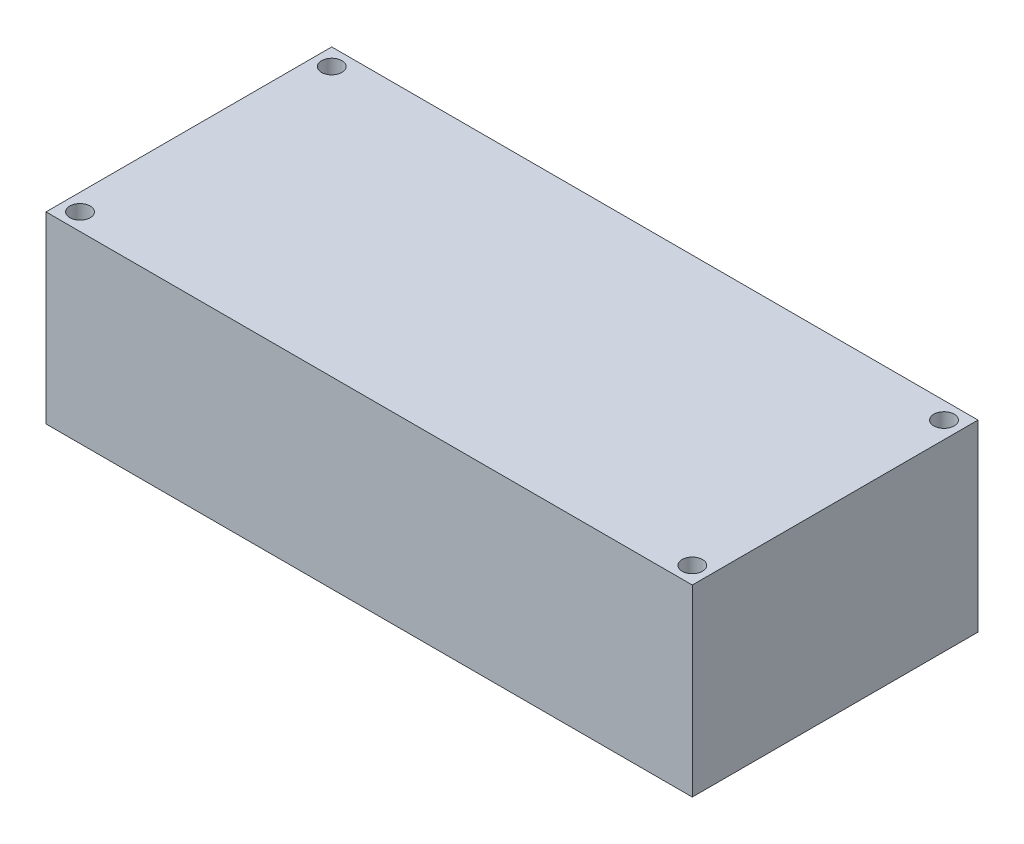
SolidWorks part; units mm, degrees
ref_plane "Front Plane" through (0, 0, 0) normal (0, 0, 1) x (1, 0, 0)
ref_plane "Top Plane" through (0, 0, 0) normal (0, 1, 0) x (1, 0, 0)
ref_plane "Right Plane" through (0, 0, 0) normal (1, 0, 0) x (0, 0, -1)
sketch "Sketch1" plane through (0, 0, 0) normal (0, 1, 0) x (1, 0, 0)
  line L0 (-46.5, 20) -> (46.5, 20) construction
  line L1 (-47.5, -21) -> (47.5, -21)
  line L2 (-47.5, -21) -> (-47.5, 21)
  line L3 (-47.5, 21) -> (47.5, 21)
  line L4 (47.5, -21) -> (47.5, 21)
  line L5 (-47.5, -21) -> (47.5, 21) construction
  line L6 (-47.5, 21) -> (47.5, -21) construction
  line L7 (45, -18.5) -> (-45, -18.5) construction
  line L8 (45, -18.5) -> (45, 18.5) construction
  line L9 (45, 18.5) -> (-45, 18.5) construction
  line L10 (-45, -18.5) -> (-45, 18.5) construction
  line L11 (45, -18.5) -> (-45, 18.5) construction
  line L12 (45, 18.5) -> (-45, -18.5) construction
  line L13 (46.5, -20) -> (46.5, 20) construction
  line L14 (-46.5, -20) -> (46.5, -20) construction
  line L15 (-46.5, -20) -> (-46.5, 20) construction
  circle A0 centre (-45, 18.5) radius 1.5
  circle A1 centre (-45, -18.5) radius 1.5
  circle A2 centre (45, 18.5) radius 1.5
  circle A3 centre (45, -18.5) radius 1.5
  point P0 (0, 0)
  point P6 (0, 0)
  dimension "D3" = 3
  dimension "D1" = 95
  dimension "D2" = 42
  dimension "D4" = 1
extrude "Boss-Extrude1" add sketch "Sketch1" along normal blind 27
